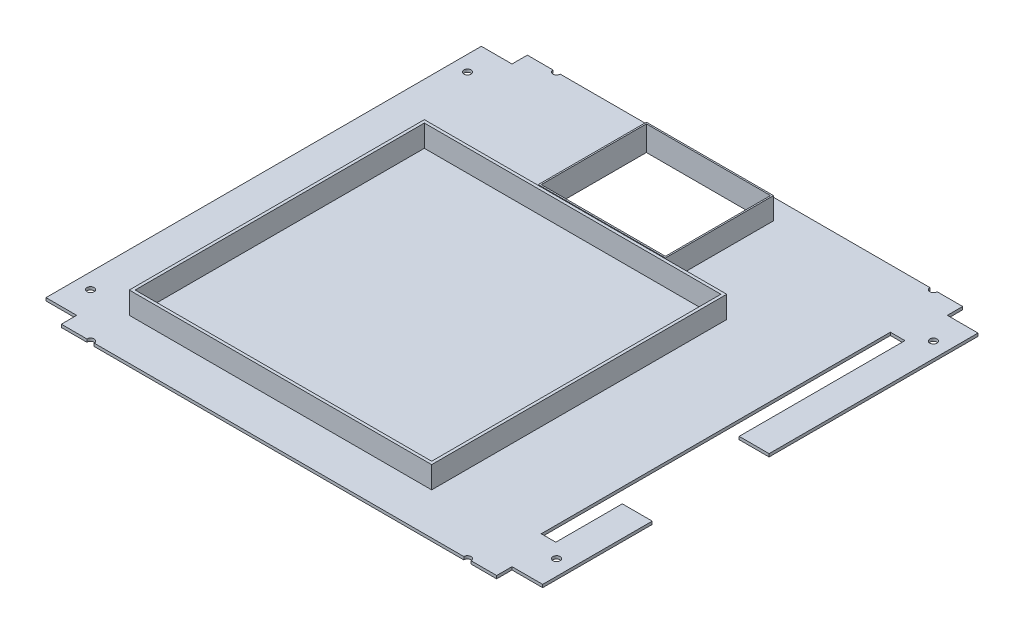
SolidWorks part; units mm, degrees
ref_plane "前视基准面" through (0, 0, 0) normal (0, 0, 1) x (1, 0, 0)
ref_plane "上视基准面" through (0, 0, 0) normal (0, 1, 0) x (1, 0, 0)
ref_plane "右视基准面" through (0, 0, 0) normal (1, 0, 0) x (0, 0, -1)
other "Configuration Table"
sketch "草图2" plane through (0, 0, 0) normal (0, 1, 0) x (1, 0, 0)
  line L9 (0, 0) -> (340, 0)
  line L10 (0, 0) -> (0, 340)
  line L11 (0, 340) -> (340, 340)
  line L12 (340, 0) -> (340, 340)
  line L13 (0, 0) -> (21, 0)
  line L14 (0, 0) -> (0, 21)
  line L15 (0, 21) -> (21, 21)
  line L16 (21, 0) -> (21, 21)
  line L17 (340, 0) -> (319, 0)
  line L18 (340, 0) -> (340, 21)
  line L19 (340, 21) -> (319, 21)
  line L20 (319, 0) -> (319, 21)
  line L21 (0, 340) -> (21, 340)
  line L22 (0, 340) -> (0, 319)
  line L23 (0, 319) -> (21, 319)
  line L24 (21, 340) -> (21, 319)
  line L25 (340, 340) -> (319, 340)
  line L26 (340, 340) -> (340, 319)
  line L27 (340, 319) -> (319, 319)
  line L28 (319, 340) -> (319, 319)
  dimension "D1" = 340
  dimension "D2" = 340
  dimension "D3" = 21
  dimension "D4" = 21
  dimension "D5" = 21
  dimension "D6" = 21
extrude "凸台-拉伸1" add sketch "草图2" along normal blind 2 contours L28 L11 L24 L23 L10 L15 L16 L9 L20 L19 L12 L27
sketch "钻孔" plane through (0, 2, 0) normal (0, 1, 0) x (1, 0, 0)
  line L0 (10.5, 319) -> (10.5, 21) construction
  line L1 (0, 319) -> (21, 319) construction
  line L2 (0, 21) -> (21, 21) construction
  line L3 (21, 10.5) -> (319, 10.5) construction
  line L4 (21, 0) -> (21, 21) construction
  line L5 (319, 0) -> (319, 21) construction
  line L6 (329.5, 21) -> (329.5, 319) construction
  line L7 (340, 21) -> (319, 21) construction
  line L8 (340, 319) -> (319, 319) construction
  line L9 (319, 329.5) -> (21, 329.5) construction
  line L10 (319, 340) -> (319, 319) construction
  line L11 (21, 340) -> (21, 319) construction
  line L12 (0, 170) -> (340, 170) construction
  line L13 (0, 21) -> (0, 319) construction
  line L14 (340, 21) -> (340, 319) construction
  line L15 (170, 340) -> (170, 0) construction
  line L16 (21, 340) -> (319, 340) construction
  line L17 (21, 0) -> (319, 0) construction
  circle A0 centre (10.5, 41) radius 2.5
  circle A1 centre (10.5, 299) radius 2.5
  circle A2 centre (329.5, 299) radius 2.5
  circle A3 centre (329.5, 41) radius 2.5
  circle A4 centre (41, 10.5) radius 2.5
  circle A5 centre (299, 10.5) radius 2.5
  circle A6 centre (299, 329.5) radius 2.5
  circle A7 centre (41, 329.5) radius 2.5
  dimension "D1" = 20
  dimension "D2" = 5
  dimension "D3" = 5
  dimension "D4" = 20
sketch "草图4" plane through (0, 2, 0) normal (0, 1, 0) x (1, 0, 0)
  line L0 (319, 329.5) -> (21, 329.5) construction
  line L1 (309.5, 289.5) -> (319.5, 289.5)
  line L2 (309.5, 289.5) -> (309.5, 50.5)
  line L3 (309.5, 50.5) -> (319.5, 50.5)
  line L4 (319.5, 289.5) -> (319.5, 50.5)
  line L5 (329.5, 21) -> (329.5, 319) construction
  line L7 (21, 10.5) -> (319, 10.5) construction
  dimension "D1" = 40
  dimension "D2" = 10
  dimension "D3" = 10
  dimension "D4" = 40
extrude "布线槽" cut sketch "草图4" against normal through all
extrude "切除-拉伸2" cut sketch "钻孔" against normal through all
sketch "草图5" plane through (0, 2, 0) normal (0, 1, 0) x (1, 0, 0)
  line L0 (21, 0) -> (319, 0) construction
  line L1 (40, 240) -> (245, 240)
  line L2 (40, 240) -> (40, 40)
  line L3 (40, 40) -> (245, 40)
  line L4 (245, 240) -> (245, 40)
  line L5 (0, 21) -> (0, 319) construction
  line L7 (21, 319) -> (319, 319) construction
  line L8 (170, 340) -> (170, 0) construction
  line L9 (21, 340) -> (319, 340) construction
  dimension "D1" = 40
  dimension "D2" = 40
  dimension "D3" = 205
  dimension "D4" = 200
extrude "拉伸-薄壁1" add sketch "草图5" along normal blind 15 thin thin type two direction wall 1 second wall 1
sketch "草图7" plane through (0, 2, 0) normal (0, 1, 0) x (1, 0, 0)
  line L0 (246, 241) -> (39, 241) construction
  line L4 (117.5, 242.5) -> (202.5, 242.5)
  line L5 (117.5, 242.5) -> (117.5, 314.5)
  line L6 (117.5, 314.5) -> (202.5, 314.5)
  line L7 (202.5, 242.5) -> (202.5, 314.5)
  line L8 (117.5, 242.5) -> (202.5, 314.5) construction
  line L9 (117.5, 314.5) -> (202.5, 242.5) construction
  point P0 (142.5, 241)
  dimension "D2" = 72
  dimension "D3" = 85
extrude "切除-拉伸4" cut sketch "草图7" against normal through all
sketch "草图9" plane through (0, 2, 0) normal (0, 1, 0) x (1, 0, 0)
  line L0 (319.5, 176) -> (340, 176)
  line L1 (319.5, 50.5) -> (319.5, 289.5) construction
  line L2 (340, 21) -> (340, 319) construction
  line L3 (340, 176) -> (340, 96)
  line L4 (340, 96) -> (319.5, 96)
  line L5 (319.5, 96) -> (319.5, 176)
  line L6 (340, 21) -> (319, 21) construction
  line L7 (21, 10.5) -> (319, 10.5)
  line L8 (21, 0) -> (21, 21) construction
  line L9 (319, 0) -> (319, 21) construction
  line L10 (319, 10.5) -> (319, 0)
  line L11 (319, 0) -> (21, 0)
  line L12 (21, 0) -> (21, 10.5)
  line L13 (319, 329.5) -> (21, 329.5)
  line L14 (319, 340) -> (319, 319) construction
  line L15 (21, 340) -> (21, 319) construction
  line L16 (21, 329.5) -> (21, 340)
  line L17 (21, 340) -> (319, 340)
  line L18 (319, 340) -> (319, 329.5)
  dimension "D1" = 75
  dimension "D2" = 80
extrude "切除-拉伸5" cut sketch "草图9" against normal blind 10
sketch "草图10" plane through (0, 2, 0) normal (0, 1, 0) x (1, 0, 0)
  line L0 (117.5, 242.5) -> (202.5, 242.5) construction
  line L1 (117.5, 314.5) -> (117.5, 242.5) construction
  line L2 (202.5, 314.5) -> (117.5, 314.5) construction
  line L3 (202.5, 242.5) -> (202.5, 314.5) construction
  line L4 (117.5, 242.5) -> (202.5, 242.5)
  line L5 (117.5, 314.5) -> (117.5, 242.5)
  line L6 (202.5, 314.5) -> (117.5, 314.5)
  line L7 (202.5, 242.5) -> (202.5, 314.5)
extrude "拉伸-薄壁2" add sketch "草图10" along normal blind 15 thin
